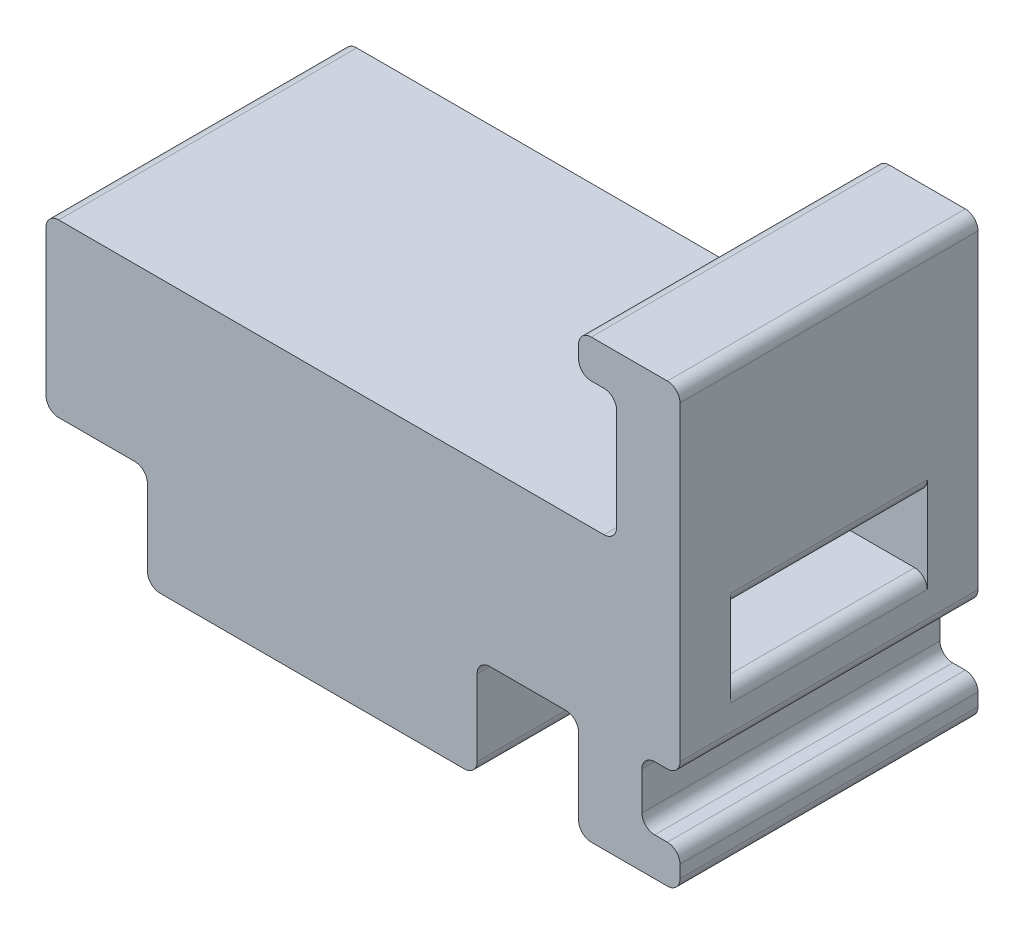
SolidWorks part; units mm, degrees
ref_plane "Front Plane" through (0, 0, 0) normal (0, 0, 1) x (1, 0, 0)
ref_plane "Top Plane" through (0, 0, 0) normal (0, 1, 0) x (1, 0, 0)
ref_plane "Right Plane" through (0, 0, 0) normal (1, 0, 0) x (0, 0, -1)
sketch "Sketch1" plane through (0, 0, 0) normal (0, 0, 1) x (1, 0, 0)
  line L2 (-25, 6.5) -> (-25, -5)
  line L4 (25, 8.5) -> (25, -5)
  line L5 (17, -7) -> (17, -11)
  line L6 (17, -11) -> (17, -13)
  line L7 (25, 16) -> (25, 8.5)
  line L13 (18, 20.5) -> (24, 20.5)
  line L14 (25, 19.5) -> (25, 16)
  line L15 (17, 19.5) -> (17, 18.5)
  line L16 (18, 17.5) -> (19, 17.5)
  line L17 (20, 16.5) -> (20, 8.5)
  line L18 (-24, 7.5) -> (19, 7.5)
  line L19 (18, -14) -> (24, -14)
  line L20 (25, -13) -> (25, -12)
  line L21 (24, -11) -> (23, -11)
  line L22 (22, -10) -> (22, -7)
  line L24 (23, -6) -> (24, -6)
  line L25 (-24, -6) -> (-18, -6)
  line L26 (-4, -14) -> (-16, -14)
  line L27 (-4, -14) -> (8, -14)
  line L28 (9, -13) -> (9, -7)
  line L29 (-17, -13) -> (-17, -7)
  line L30 (10, -6) -> (16, -6)
  line L31 (-25, 0.75) -> (-27.8717, 0.75) construction
  line L32 (-27.8717, 0.75) -> (-27.8717, 7.5) construction
  line L33 (-27.8717, 0.75) -> (-29.26, 0.75)
  line L34 (-29.26, 0.75) -> (-29.26, 3.5)
  line L35 (-29.26, 3.5) -> (-29.26, 7.5) construction
  arc A1 (25, 19.5) -> (24, 20.5) centre (24, 19.5) ccw
  arc A2 (17, 19.5) -> (18, 20.5) centre (18, 19.5) cw
  arc A3 (18, 17.5) -> (17, 18.5) centre (18, 18.5) cw
  arc A4 (20, 16.5) -> (19, 17.5) centre (19, 16.5) ccw
  arc A5 (20, 8.5) -> (19, 7.5) centre (19, 8.5) cw
  arc A6 (25, -5) -> (24, -6) centre (24, -5) cw
  arc A7 (23, -6) -> (22, -7) centre (23, -7) ccw
  arc A8 (23, -11) -> (22, -10) centre (23, -10) cw
  arc A9 (25, -12) -> (24, -11) centre (24, -12) ccw
  arc A10 (25, -13) -> (24, -14) centre (24, -13) cw
  arc A11 (18, -14) -> (17, -13) centre (18, -13) cw
  arc A12 (17, -7) -> (16, -6) centre (16, -7) ccw
  arc A13 (-25, -5) -> (-24, -6) centre (-24, -5) ccw
  arc A14 (-25, 6.5) -> (-24, 7.5) centre (-24, 6.5) cw
  arc A15 (9, -7) -> (10, -6) centre (10, -7) cw
  arc A16 (9, -13) -> (8, -14) centre (8, -13) cw
  arc A17 (-16, -14) -> (-17, -13) centre (-16, -13) cw
  arc A18 (-17, -7) -> (-18, -6) centre (-18, -7) ccw
  point P0 (0, 0)
  point P25 (17, 17.5)
  dimension "D1" = 1
extrude "Boss-Extrude2" add sketch "Sketch1" along normal mid plane 23.5 contours L18 A5 L17 A4 L16 A3 L15 A2 L13 A1 L14 L7 L4 A6 L24 A7 L22 A8 L21 A9 L20 A10 L19 A11 L6 L5 A12 L30 A15 L28 A16 L27 L26 A17 L29 A18 L25 A13 L2 A14
sketch "Sketch5" plane through (-25, 0, 0) normal (-1, 0, 0) x (0, 0, 1)
  line L2 (-7.75, 3.5) -> (7.75, 3.5)
  line L3 (-7.75, 3.5) -> (-7.75, -2)
  line L4 (-7.75, -2) -> (7.75, -2)
  line L5 (7.75, 3.5) -> (7.75, -2)
  point P4 (0, 0.75)
extrude "Cut-Extrude2" cut sketch "Sketch5" against normal through all contours L2 L5 L4 L3
fillet "Fillet1" radius 1 4 edges at (25, -2, 0) (25, 3.5, 0) (-25, -2, 0) (-25, 3.5, 0)
sketch "Sketch7" plane through (0, -14, 0) normal (0, -1, 0) x (1, 0, 0)
  circle A0 centre (-4, 0) radius 10.25
extrude "Cut-Extrude3" cut sketch "Sketch7" against normal mid plane 15
